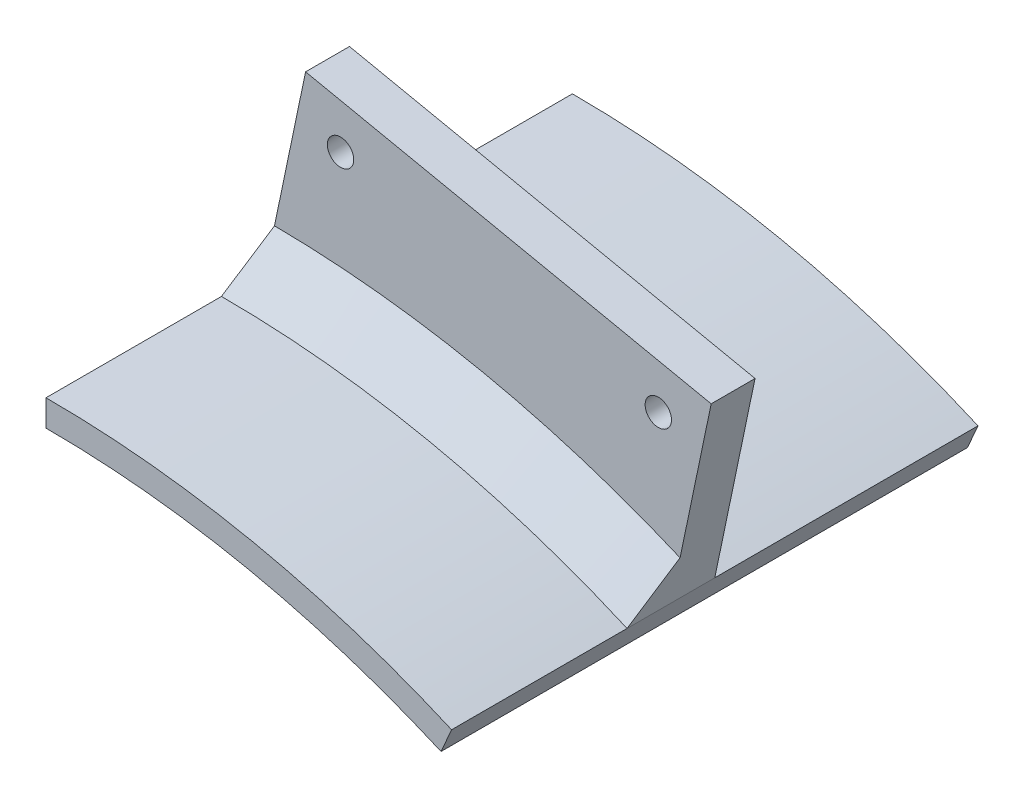
SolidWorks part; units mm, degrees
ref_plane "前视基准面" through (0, 0, 0) normal (0, 0, 1) x (1, 0, 0)
ref_plane "上视基准面" through (0, 0, 0) normal (0, 1, 0) x (1, 0, 0)
ref_plane "右视基准面" through (0, 0, 0) normal (1, 0, 0) x (0, 0, -1)
sketch "草图1" plane through (0, 0, 0) normal (0, 0, 1) x (1, 0, 0)
  line L0 (0, 112.5) -> (0, 115.5)
  line L1 (45.0284, 103.0956) -> (46.2292, 105.8448)
  arc A0 (45.0284, 103.0956) -> (0, 112.5) centre (0, 0) ccw
  arc A1 (46.2292, 105.8448) -> (0, 115.5) centre (0, 0) ccw
  point P6 (0, 112.5)
  point P7 (45.0284, 103.0956)
  dimension "D1" = 225
  dimension "D2" = 3
  dimension "D3" = 46
extrude "凸台-拉伸1" add sketch "草图1" along normal blind 60
ref_plane "基准面1" through (0, 0, 35) normal (0, 0, -1) x (-1, 0, 0)
sketch "草图2" plane through (0, 0, 35) normal (0, 0, -1) x (-1, 0, 0)
  line L0 (-27.7022, 132.638) -> (-4.5876, 137.4656)
  line L1 (-4.5876, 137.4656) -> (0, 115.5)
  line L2 (-23.6133, 113.0604) -> (-28.2118, 135.0777) construction
  line L3 (-50.8168, 127.8104) -> (-46.2292, 105.8448)
  line L4 (-27.7022, 132.638) -> (-50.8168, 127.8104)
  arc A0 (0, 115.5) -> (-46.2292, 105.8448) centre (0, 0) ccw construction
  arc A1 (0, 115.5) -> (-46.2292, 105.8448) centre (0, 0) ccw
  circle A2 centre (-8.5708, 131.5258) radius 1.5
  circle A3 centre (-44.7892, 123.9614) radius 1.5
  dimension "D3" = 3
  dimension "D1" = 20
  dimension "D2" = 18.5
  dimension "D4" = 5
extrude "凸台-拉伸2" add sketch "草图2" along normal blind 5
chamfer "倒角1" distance 5 angle 45 1 edges at (23.6133, 113.0604, 35)
